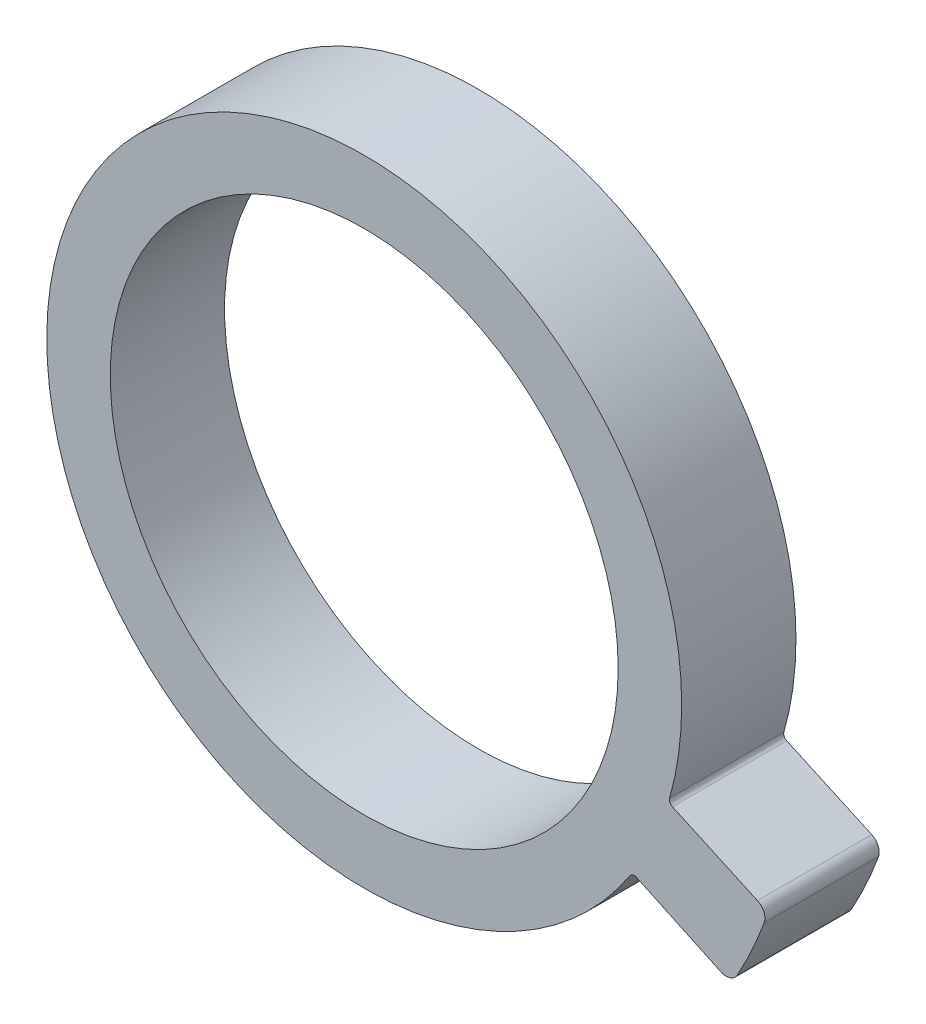
SolidWorks part; units mm, degrees
material "Chêne"
ref_plane "Plan de face" through (0, 0, 0) normal (0, 0, 1) x (1, 0, 0)
ref_plane "Plan de dessus" through (0, 0, 0) normal (0, 1, 0) x (1, 0, 0)
ref_plane "Plan de droite" through (0, 0, 0) normal (1, 0, 0) x (0, 0, -1)
sketch "Esquisse1" plane through (0, 0, 0) normal (0, 0, 1) x (1, 0, 0)
  line L0 (15.4852, -5.1767) -> (12.1342, -3.6507)
  line L1 (14.0407, -8.3254) -> (10.7168, -6.7654)
  arc A0 (12.0247, -3.4141) -> (10.4644, -6.8371) centre (0, 0) ccw
  arc A1 (15.7471, -5.8046) -> (14.6908, -8.1145) centre (0, 0) cw
  arc A2 (15.7471, -5.8046) -> (15.4852, -5.1767) centre (15.278, -5.6317) ccw
  arc A3 (14.0407, -8.3254) -> (14.6908, -8.1145) centre (14.2532, -7.8727) ccw
  circle A4 centre (0, 0) radius 10
  arc A5 (12.1342, -3.6507) -> (12.0247, -3.4141) centre (12.2171, -3.4687) cw
  arc A6 (10.7168, -6.7654) -> (10.4644, -6.8371) centre (10.6319, -6.9465) ccw
  point P116 (0, 0)
  point P374 (0, 0)
extrude "Boss.-Extru.3" add sketch "Esquisse1" along normal blind 4.5
